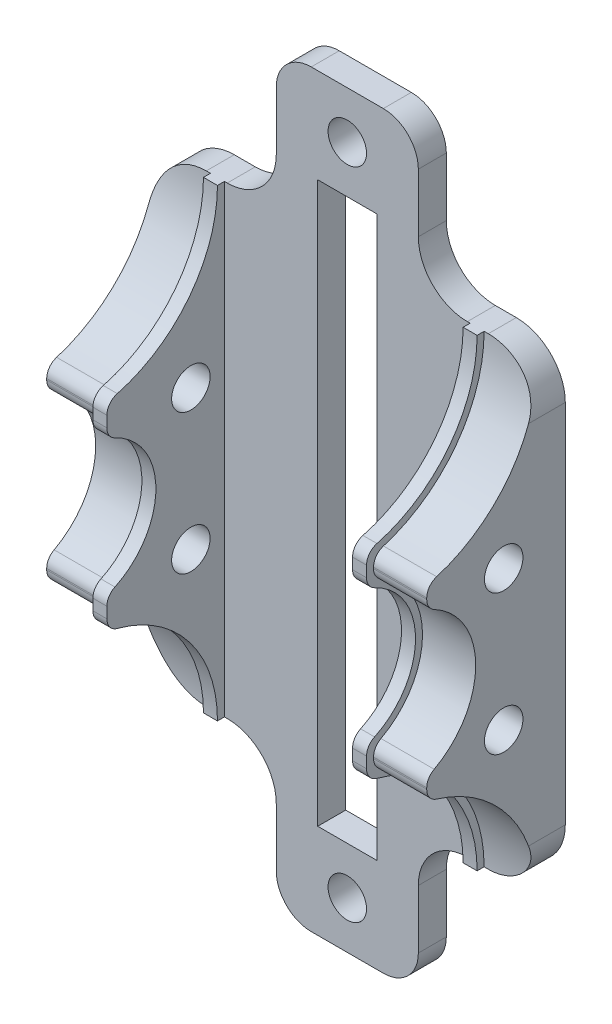
SolidWorks part; units mm, degrees
ref_plane "Front Plane" through (0, 0, 0) normal (0, 0, 1) x (1, 0, 0)
ref_plane "Top Plane" through (0, 0, 0) normal (0, 1, 0) x (1, 0, 0)
ref_plane "Right Plane" through (0, 0, 0) normal (1, 0, 0) x (0, 0, -1)
sketch "Sketch1" plane through (0, 0, 0) normal (0, 0, 1) x (1, 0, 0)
  line L20 (-62.15, 75) -> (-69.55, 75)
  line L21 (-69.55, 75) -> (-69.55, 65.75)
  line L22 (-69.55, 65.75) -> (-62.15, 65.75)
  line L23 (-62.15, 65.75) -> (-62.15, 64.25)
  line L24 (-62.15, 64.25) -> (-69.55, 64.25)
  line L25 (-69.55, 64.25) -> (-69.55, 55)
  line L26 (-69.55, 55) -> (-62.15, 55)
  line L27 (-62.15, 55) -> (-62.15, 11.5)
  line L28 (-62.15, 11.5) -> (-41.85, 11.5)
  line L29 (-41.85, 11.5) -> (-41.85, 55)
  line L30 (-41.85, 55) -> (-34.45, 55)
  line L31 (-34.45, 55) -> (-34.45, 64.25)
  line L32 (-34.45, 64.25) -> (-41.85, 64.25)
  line L33 (-41.85, 64.25) -> (-41.85, 65.75)
  line L34 (-41.85, 65.75) -> (-34.45, 65.75)
  line L35 (-34.45, 65.75) -> (-34.45, 75)
  line L36 (-34.45, 75) -> (-41.85, 75)
  line L37 (-41.85, 75) -> (-41.85, 118.5)
  line L38 (-41.85, 118.5) -> (-62.15, 118.5)
  line L39 (-62.15, 118.5) -> (-62.15, 75)
  line L40 (-62.15, 75) -> (-69.55, 75)
  line L41 (-69.55, 75) -> (-69.55, 65.75)
  line L42 (-69.55, 65.75) -> (-62.15, 65.75)
  line L43 (-62.15, 65.75) -> (-62.15, 64.25)
  line L44 (-62.15, 64.25) -> (-69.55, 64.25)
  line L45 (-69.55, 64.25) -> (-69.55, 55)
  line L46 (-69.55, 55) -> (-62.15, 55)
  line L47 (-62.15, 55) -> (-62.15, 11.5)
  line L48 (-62.15, 11.5) -> (-41.85, 11.5)
  line L49 (-41.85, 11.5) -> (-41.85, 55)
  line L50 (-41.85, 55) -> (-34.45, 55)
  line L51 (-34.45, 55) -> (-34.45, 64.25)
  line L52 (-34.45, 64.25) -> (-41.85, 64.25)
  line L53 (-41.85, 64.25) -> (-41.85, 65.75)
  line L54 (-41.85, 65.75) -> (-34.45, 65.75)
  line L55 (-34.45, 65.75) -> (-34.45, 75)
  line L56 (-34.45, 75) -> (-41.85, 75)
  line L57 (-41.85, 75) -> (-41.85, 118.5)
  line L58 (-41.85, 118.5) -> (-62.15, 118.5)
  line L59 (-62.15, 118.5) -> (-62.15, 75)
  circle A0 centre (-52, 111.75) radius 2.75 construction
  circle A1 centre (-52, 18.25) radius 2.75 construction
  circle A2 centre (-52, 111.75) radius 2.75
  circle A3 centre (-52, 18.25) radius 2.75
  dimension "D1" = 0
extrude "Boss-Extrude1" add sketch "Sketch1" along normal blind 4
fillet "Fillet1" radius 5 4 edges at (-62.15, 118.5, 2) (-41.85, 118.5, 2) (-62.15, 11.5, 2) (-41.85, 11.5, 2)
sketch "Sketch3" plane through (-34.45, 0, 0) normal (1, 0, 0) x (0, 0, -1)
  line L0 (-4, 65) -> (-4, 105)
  line L1 (-4, 64.25) -> (-4, 65.75) construction
  line L2 (-4, 65) -> (-24, 65)
  line L3 (-12.8, 65) -> (-19.8, 65)
  line L4 (-19.8, 65) -> (-19.8, 75.3827)
  line L5 (-19.8, 75.3827) -> (-19.8, 54.6173)
  line L6 (-19.8, 75.3827) -> (-19.8, 78.3827)
  line L7 (-19.8, 54.6173) -> (-19.8, 51.6173)
  line L8 (-4, 105) -> (-8.121, 105)
  line L9 (-19.8, 78.3827) -> (-19.8, 118.3827)
  line L10 (-19.8, 118.3827) -> (-49.8, 118.3827)
  line L11 (-4, 105) -> (-4, 26.6105)
  line L12 (-4, 16.5) -> (-4, 55) construction
  arc A0 (-19.8, 54.6173) -> (-19.8, 75.3827) centre (-24, 65) ccw
  arc A1 (-19.8, 78.3827) -> (-24.2472, 118.3827) centre (-24.2472, 98.1355) ccw
  circle A2 centre (-24.2472, 31.8645) radius 20.2472
  line M4 (-4, 75) -> (-4, 65.75)
  dimension "D3" = 22.4
  dimension "D1" = 40
  dimension "D2" = 20
  dimension "D4" = 7
  dimension "D5" = 3
  dimension "D6" = 3
  dimension "D7" = 40
  dimension "D8" = 30
extrude "Boss-Extrude3" add sketch "Sketch3" along normal blind 9.6 separate body contours A1 L6 A0 L2 L0 M4 | L7 A2 L11 L2 A0
sketch "Sketch5" plane through (-34.45, 0, 0) normal (-1, 0, 0) x (0, 0, 1)
  line L3 (4, 98.1355) -> (4, 31.8645)
  line L4 (19.8, 51.6173) -> (19.8, 54.6173)
  line L5 (19.8, 75.3827) -> (19.8, 78.3827)
  line L6 (4, 98.1355) -> (4, 31.8645)
  line L7 (19.8, 51.6173) -> (19.8, 54.6173)
  line L8 (19.8, 75.3827) -> (19.8, 78.3827)
  arc A3 (4, 98.1355) -> (19.8, 78.3827) centre (24.2472, 98.1355) ccw
  arc A4 (19.8, 51.6173) -> (4, 31.8645) centre (24.2472, 31.8645) ccw
  arc A5 (19.8, 75.3827) -> (19.8, 54.6173) centre (24, 65) ccw
  arc A6 (4, 98.1355) -> (19.8, 78.3827) centre (24.2472, 98.1355) ccw
  arc A7 (19.8, 51.6173) -> (4, 31.8645) centre (24.2472, 31.8645) ccw
  arc A8 (19.8, 75.3827) -> (19.8, 54.6173) centre (24, 65) ccw
  dimension "D1" = 0
extrude "Boss-Extrude4" add sketch "Sketch5" along normal blind 10
sketch "Sketch6" plane through (0, 0, 4) normal (0, 0, -1) x (-1, 0, 0)
  line L12 (24.85, 31.8645) -> (41.85, 31.8645)
  line L13 (41.85, 31.8645) -> (41.85, 55)
  line L14 (41.85, 55) -> (34.45, 55)
  line L15 (34.45, 55) -> (34.45, 64.25)
  line L16 (34.45, 64.25) -> (41.85, 64.25)
  line L17 (41.85, 64.25) -> (41.85, 65.75)
  line L18 (41.85, 65.75) -> (34.45, 65.75)
  line L19 (34.45, 65.75) -> (34.45, 75)
  line L20 (34.45, 75) -> (41.85, 75)
  line L21 (41.85, 75) -> (41.85, 98.1355)
  line L22 (41.85, 98.1355) -> (24.85, 98.1355)
  line L23 (24.85, 98.1355) -> (24.85, 31.8645)
  line L24 (24.85, 31.8645) -> (41.85, 31.8645)
  line L25 (41.85, 31.8645) -> (41.85, 55)
  line L26 (41.85, 55) -> (34.45, 55)
  line L27 (34.45, 55) -> (34.45, 64.25)
  line L28 (34.45, 64.25) -> (41.85, 64.25)
  line L29 (41.85, 64.25) -> (41.85, 65.75)
  line L30 (41.85, 65.75) -> (34.45, 65.75)
  line L31 (34.45, 65.75) -> (34.45, 75)
  line L32 (34.45, 75) -> (41.85, 75)
  line L33 (41.85, 75) -> (41.85, 98.1355)
  line L34 (41.85, 98.1355) -> (24.85, 98.1355)
  line L35 (24.85, 98.1355) -> (24.85, 31.8645)
  dimension "D1" = 0
extrude "Boss-Extrude5" add sketch "Sketch6" along normal up to surface (4 mm away) up to face at (-49.25, 111.75, 0)
sketch "Sketch7" plane through (0, 0, 19.8) normal (0, 0, 1) x (1, 0, 0)
  line L0 (-31.85, 76) -> (-31.85, 98.1355)
  line L1 (-41.85, 98.1355) -> (-24.85, 98.1355) construction
  line L2 (-31.85, 98.1355) -> (-32.45, 98.1355)
  line L3 (-32.45, 98.1355) -> (-32.45, 31.8645)
  line L4 (-41.85, 31.8645) -> (-24.85, 31.8645) construction
  line L5 (-32.45, 31.8645) -> (-31.85, 31.8645)
  dimension "D1" = 0.6
  dimension "D2" = 0.6
sketch "Sketch9" plane through (-44.45, 0, 0) normal (-1, 0, 0) x (0, 0, 1)
  line L17 (5, 31.8645) -> (4, 31.8645)
  line L18 (4, 55) -> (4, 16.5) construction
  line L19 (20.8, 79.1995) -> (20.8, 74.685)
  line L20 (20.8, 55.315) -> (20.8, 50.8005)
  line L21 (20.8, 79.1995) -> (20.8, 74.685)
  line L22 (20.8, 55.315) -> (20.8, 50.8005)
  line L23 (5, 98.1355) -> (4, 98.1355)
  line L24 (4, 98.1355) -> (4, 31.8645)
  line L25 (19.8, 75.3827) -> (19.8, 78.3827) construction
  line L26 (19.8, 51.6173) -> (19.8, 54.6173) construction
  line L27 (19.8, 75.3827) -> (19.8, 78.3827)
  line L28 (19.8, 51.6173) -> (19.8, 54.6173)
  arc A11 (20.175, 74.4557) -> (20.175, 55.5443) centre (24, 65) ccw
  arc A12 (20.175, 74.4557) -> (20.175, 55.5443) centre (24, 65) ccw
  arc A19 (4, 98.1355) -> (19.8, 78.3827) centre (24.2472, 98.1355) ccw construction
  arc A20 (19.8, 75.3827) -> (19.8, 54.6173) centre (24, 65) ccw construction
  arc A21 (19.8, 51.6173) -> (4, 31.8645) centre (24.2472, 31.8645) ccw construction
  arc A22 (20.8, 74.685) -> (20.8, 55.315) centre (24, 65) ccw
  arc A23 (5, 98.1355) -> (20.8, 79.1995) centre (24.2472, 98.1355) ccw
  arc A24 (20.8, 50.8005) -> (5, 31.8645) centre (24.2472, 31.8645) ccw
  arc A25 (20.8, 74.685) -> (20.8, 55.315) centre (24, 65) ccw
  arc A26 (5, 98.1355) -> (20.8, 79.1995) centre (24.2472, 98.1355) ccw
  arc A27 (20.8, 50.8005) -> (5, 31.8645) centre (24.2472, 31.8645) ccw
  arc A28 (4, 98.1355) -> (19.8, 78.3827) centre (24.2472, 98.1355) ccw
  arc A29 (19.8, 75.3827) -> (19.8, 54.6173) centre (24, 65) ccw
  arc A30 (19.8, 51.6173) -> (4, 31.8645) centre (24.2472, 31.8645) ccw
  arc M7 (19.8, 78.3827) -> (4, 98.1355) centre (24.2472, 98.1355) cw
  arc M9 (4, 31.8645) -> (19.8, 51.6173) centre (24.2472, 31.8645) cw
  line M10 (19.8, 51.6173) -> (19.8, 54.6173)
  arc M11 (19.8, 54.6173) -> (19.8, 75.3827) centre (24, 65) cw
  line M12 (19.8, 75.3827) -> (19.8, 78.3827)
  dimension "D1" = 1
  dimension "D2" = 1
extrude "Boss-Extrude6" add sketch "Sketch9" against normal blind 12 contours A27 L22 A25 A12 L21 A26 L23 L17 M7 M12 M11 M10 M9
sketch "Sketch10" plane through (-44.45, 0, 0) normal (-1, 0, 0) x (0, 0, 1)
  line L5 (4, 98.1355) -> (4, 31.8645)
  line L6 (4, 31.8645) -> (5, 31.8645)
  line L7 (20.8, 50.8005) -> (20.8, 55.315)
  line L8 (20.8, 74.685) -> (20.8, 79.1995)
  line L9 (5, 98.1355) -> (4, 98.1355)
  line L10 (4, 98.1355) -> (4, 31.8645)
  line L11 (4, 31.8645) -> (5, 31.8645)
  line L12 (20.8, 50.8005) -> (20.8, 55.315)
  line L13 (20.8, 74.685) -> (20.8, 79.1995)
  line L14 (5, 98.1355) -> (4, 98.1355)
  arc A3 (20.8, 50.8005) -> (5, 31.8645) centre (24.2472, 31.8645) ccw
  arc A4 (20.8, 74.685) -> (20.8, 55.315) centre (24, 65) ccw
  arc A5 (5, 98.1355) -> (20.8, 79.1995) centre (24.2472, 98.1355) ccw
  arc A6 (20.8, 50.8005) -> (5, 31.8645) centre (24.2472, 31.8645) ccw
  arc A7 (20.8, 74.685) -> (20.8, 55.315) centre (24, 65) ccw
  arc A8 (5, 98.1355) -> (20.8, 79.1995) centre (24.2472, 98.1355) ccw
  dimension "D1" = 0
extrude "Cut-Extrude1" cut sketch "Sketch10" against normal blind 10
sketch "Sketch12" plane through (0, 0, 4) normal (0, 0, 1) x (1, 0, 0)
  line L0 (-41.85, 31.8645) -> (-62.15, 31.8645)
  line L1 (-62.15, 55) -> (-62.15, 16.5) construction
  line L2 (-62.15, 31.8645) -> (-79.15, 31.8645)
  line L3 (-32.45, 98.1355) -> (-62.15, 98.1355)
  line L4 (-62.15, 113.5) -> (-62.15, 75) construction
  line L5 (-62.15, 98.1355) -> (-79.15, 98.1355)
  line L6 (-79.15, 31.8645) -> (-79.15, 98.1355)
  line L7 (-62.15, 98.1355) -> (-62.15, 31.8645)
  line M11 (-62.15, 113.5) -> (-62.15, 75)
  line M12 (-62.15, 75) -> (-69.55, 75)
  line M13 (-69.55, 75) -> (-69.55, 65.75)
  line M14 (-69.55, 65.75) -> (-62.15, 65.75)
  line M15 (-62.15, 65.75) -> (-62.15, 64.25)
  line M16 (-62.15, 64.25) -> (-69.55, 64.25)
  line M17 (-69.55, 64.25) -> (-69.55, 55)
  line M18 (-69.55, 55) -> (-62.15, 55)
  line M19 (-62.15, 55) -> (-62.15, 16.5)
  dimension "D1" = 17
  dimension "D2" = 17
extrude "Boss-Extrude7" add sketch "Sketch12" against normal up to surface (4 mm away) contours L6 L2 L5 M19 M18 M17 M16 M15 M14 M13 M12 M11 up to face at (-49.25, 111.75, 0)
sketch "Sketch13" plane through (-79.15, 0, 0) normal (-1, 0, 0) x (0, 0, 1)
  line L5 (19.8, 75.3827) -> (19.8, 78.3827)
  line L6 (19.8, 51.6173) -> (19.8, 54.6173)
  line L7 (0, 31.8645) -> (4, 31.8645)
  line L8 (0, 98.1355) -> (0, 31.8645)
  line L9 (4, 98.1355) -> (0, 98.1355)
  line L10 (19.8, 75.3827) -> (19.8, 78.3827)
  line L11 (19.8, 51.6173) -> (19.8, 54.6173)
  line L12 (0, 31.8645) -> (4, 31.8645)
  line L13 (0, 98.1355) -> (0, 31.8645)
  line L14 (4, 98.1355) -> (0, 98.1355)
  arc A3 (4, 98.1355) -> (19.8, 78.3827) centre (24.2472, 98.1355) ccw
  arc A4 (19.8, 75.3827) -> (19.8, 54.6173) centre (24, 65) ccw
  arc A5 (19.8, 51.6173) -> (4, 31.8645) centre (24.2472, 31.8645) ccw
  arc A6 (4, 98.1355) -> (19.8, 78.3827) centre (24.2472, 98.1355) ccw
  arc A7 (19.8, 75.3827) -> (19.8, 54.6173) centre (24, 65) ccw
  arc A8 (19.8, 51.6173) -> (4, 31.8645) centre (24.2472, 31.8645) ccw
  dimension "D1" = 0
extrude "Boss-Extrude8" add sketch "Sketch13" against normal blind 7.6
sketch "Sketch14" plane through (-71.55, 0, 0) normal (1, 0, 0) x (0, 0, -1)
  line L5 (-4, 98.1355) -> (-5, 98.1355)
  line L6 (-4, 31.8645) -> (-4, 98.1355)
  line L7 (-5, 31.8645) -> (-4, 31.8645)
  line L8 (-20.8, 55.315) -> (-20.8, 50.8005)
  line L9 (-20.8, 79.1995) -> (-20.8, 74.685)
  line L10 (-4, 98.1355) -> (-5, 98.1355)
  line L11 (-4, 31.8645) -> (-4, 98.1355)
  line L12 (-5, 31.8645) -> (-4, 31.8645)
  line L13 (-20.8, 55.315) -> (-20.8, 50.8005)
  line L14 (-20.8, 79.1995) -> (-20.8, 74.685)
  arc A3 (-5, 31.8645) -> (-20.8, 50.8005) centre (-24.2472, 31.8645) ccw
  arc A4 (-20.8, 55.315) -> (-20.8, 74.685) centre (-24, 65) ccw
  arc A5 (-20.8, 79.1995) -> (-5, 98.1355) centre (-24.2472, 98.1355) ccw
  arc A6 (-5, 31.8645) -> (-20.8, 50.8005) centre (-24.2472, 31.8645) ccw
  arc A7 (-20.8, 55.315) -> (-20.8, 74.685) centre (-24, 65) ccw
  arc A8 (-20.8, 79.1995) -> (-5, 98.1355) centre (-24.2472, 98.1355) ccw
  dimension "D1" = 0
extrude "Boss-Extrude9" add sketch "Sketch14" along normal blind 2
fillet "Fillet2" radius 7 8 edges at (-79.15, 98.1355, 2) (-62.15, 98.1355, 2) (-41.85, 98.1355, 2) (-24.85, 98.1355, 2) (-24.85, 31.8645, 2) (-79.15, 31.8645, 2) (-62.15, 31.8645, 2) (-41.85, 31.8645, 2)
sketch "Sketch15" plane through (0, 0, 0) normal (0, 0, -1) x (-1, 0, 0)
  line L1 (47.775, 25) -> (56.225, 25)
  line L2 (47.775, 25) -> (47.775, 105)
  line L3 (47.775, 105) -> (56.225, 105)
  line L4 (56.225, 25) -> (56.225, 105)
extrude "Cut-Extrude2" cut sketch "Sketch15" against normal blind 14
fillet "Fillet3" radius 2 16 edges at (-70.55, 79.1995, 20.8) (-70.55, 74.685, 20.8) (-33.45, 79.1995, 20.8) (-28.65, 75.3827, 19.8) (-28.65, 78.3827, 19.8) (-33.45, 74.685, 20.8) (-33.45, 50.8005, 20.8) (-33.45, 55.315, 20.8) (-28.65, 54.6173, 19.8) (-28.65, 51.6173, 19.8) (-75.35, 78.3827, 19.8) (-75.35, 75.3827, 19.8) (-75.35, 54.6173, 19.8) (-75.35, 51.6173, 19.8) (-70.55, 55.315, 20.8) (-70.55, 50.8005, 20.8)
sketch "Sketch17" plane through (-24.85, 0, 0) normal (1, 0, 0) x (0, 0, -1)
  line L0 (-12.8, 65) -> (-4.8, 65)
  line L2 (-8.8, 65) -> (-8.8, 75)
  arc A0 (-18.7394, 55.1123) -> (-18.7394, 74.8877) centre (-24, 65) ccw construction
  circle A1 centre (-8.8, 75) radius 2.75
  circle A2 centre (-8.8, 55) radius 2.75
  dimension "D2" = 5.5
  dimension "D1" = 10
  dimension "D3" = 8
extrude "Cut-Extrude4" cut sketch "Sketch17" against normal through all both and the other way through all
